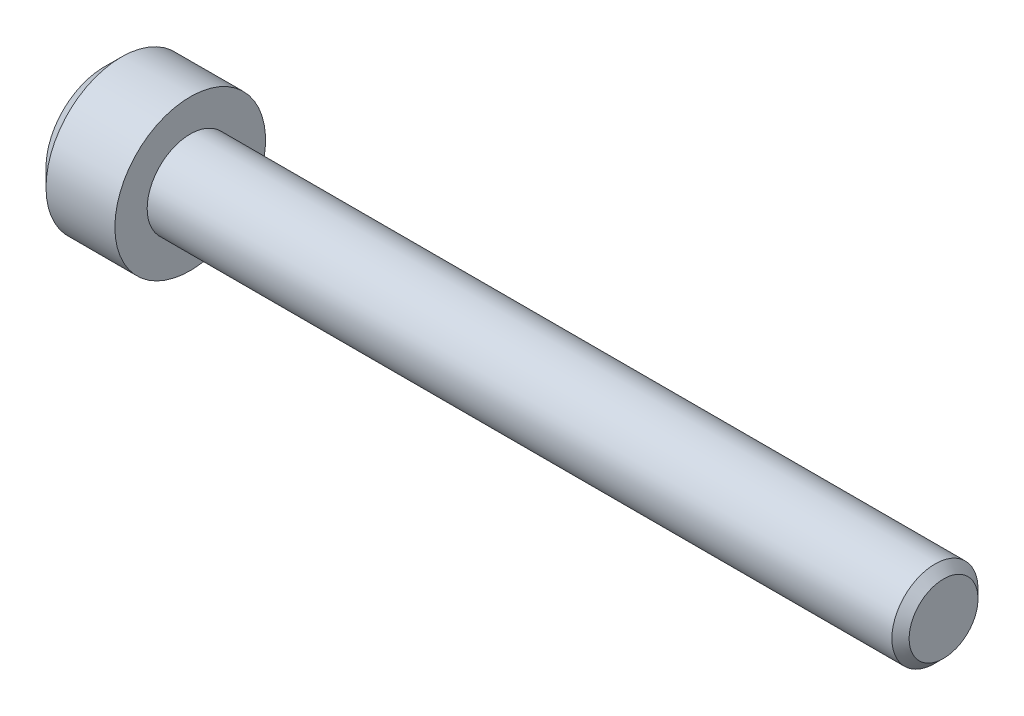
SolidWorks part; units mm, degrees
ref_plane "前视基准面" through (0, 0, 0) normal (0, 0, 1) x (1, 0, 0)
ref_plane "上视基准面" through (0, 0, 0) normal (0, 1, 0) x (1, 0, 0)
ref_plane "右视基准面" through (0, 0, 0) normal (1, 0, 0) x (0, 0, -1)
sketch "草图1" plane through (0, 0, 0) normal (0, 0, 1) x (1, 0, 0)
  line L0 (0, 0) -> (0, 2)
  line L1 (0, 2) -> (-35, 2)
  line L2 (-35, 2) -> (-35, 3.5)
  line L3 (-35, 3.5) -> (-39, 3.5)
  line L4 (-39, 3.5) -> (-39, 0)
  line L5 (-39, 0) -> (0, 0)
  line L6 (0, 0) -> (4.7488, 0) construction
  dimension "D1" = 4
  dimension "D2" = 35
  dimension "D3" = 4
  dimension "D4" = 7
revolve "旋转1" add sketch "草图1" angle 360 about L6
cosmetic thread "装饰螺纹线1" parameters "D1"=20, "D2"=3.44
chamfer "倒角1" distance 0.4 angle 45 1 edges at (0, 0, 2)
sketch "草图2" plane through (-39, 0, 0) normal (-1, 0, 0) x (0, 0, 1)
  line L1 (0, 1.7321) -> (-1.5, 0.866)
  line L2 (-1.5, 0.866) -> (-1.5, -0.866)
  line L3 (-1.5, -0.866) -> (0, -1.7321)
  line L4 (0, -1.7321) -> (1.5, -0.866)
  line L5 (1.5, -0.866) -> (1.5, 0.866)
  line L6 (1.5, 0.866) -> (0, 1.7321)
  circle A0 centre (0, 0) radius 1.5 construction
  dimension "D1" = 3
extrude "切除-拉伸1" cut sketch "草图2" against normal blind 2
chamfer "倒角2" distance 0.8 angle 45 1 edges at (-39, 0, 3.5)
sketch "草图4" plane through (-37, 0, 0) normal (-1, 0, 0) x (0, 0, 1)
  line L1 (0, -1.7321) -> (1.5, -0.866)
  line L2 (1.5, -0.866) -> (1.5, 0.866)
  line L3 (1.5, 0.866) -> (0, 1.7321)
  line L4 (0, 1.7321) -> (-1.5, 0.866)
  line L5 (-1.5, 0.866) -> (-1.5, -0.866)
  line L6 (1.5, 0.866) -> (0, 1.7321)
  line L7 (0, 1.7321) -> (-1.5, 0.866)
  line L8 (-1.5, 0.866) -> (-1.5, -0.866)
  line L9 (-1.5, -0.866) -> (0, -1.7321)
  line L10 (0, -1.7321) -> (1.5, -0.866)
  line L11 (1.5, -0.866) -> (1.5, 0.866)
  line L12 (1.5, 0.866) -> (0, 1.7321) construction
  line L13 (0, 1.7321) -> (-1.5, 0.866) construction
  line L14 (-1.5, 0.866) -> (-1.5, -0.866) construction
  line L15 (-1.5, -0.866) -> (0, -1.7321) construction
  line L16 (0, -1.7321) -> (1.5, -0.866) construction
  line L17 (1.5, -0.866) -> (1.5, 0.866) construction
  line L18 (-1.5, -0.866) -> (0, -1.7321)
  circle A0 centre (0, 0) radius 1.5 construction
  dimension "D1" = 0
extrude "切除-拉伸2" cut sketch "草图4" against normal through all draft 59
